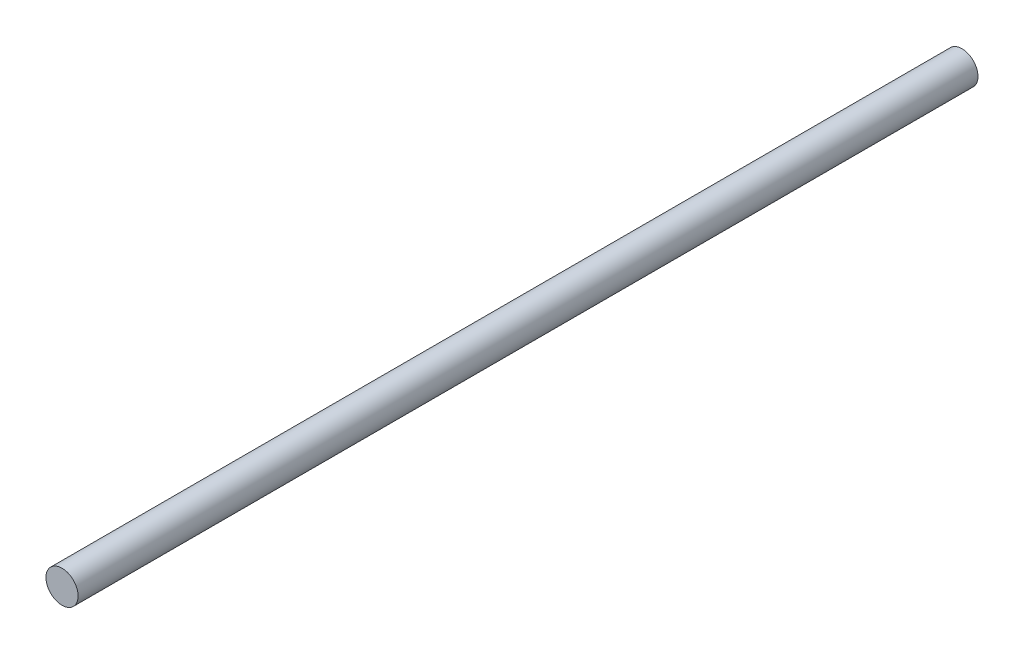
SolidWorks part; units mm, degrees
ref_plane "Alzado" through (0, 0, 0) normal (0, 0, 1) x (1, 0, 0)
ref_plane "Planta" through (0, 0, 0) normal (0, 1, 0) x (1, 0, 0)
ref_plane "Vista lateral" through (0, 0, 0) normal (1, 0, 0) x (0, 0, -1)
sketch "Croquis1" plane through (0, 0, 0) normal (0, 0, 1) x (1, 0, 0)
  circle A0 centre (0, 0) radius 12.5
  dimension "D1" = 25
extrude "Saliente-Extruir1" add sketch "Croquis1" along normal blind 700
